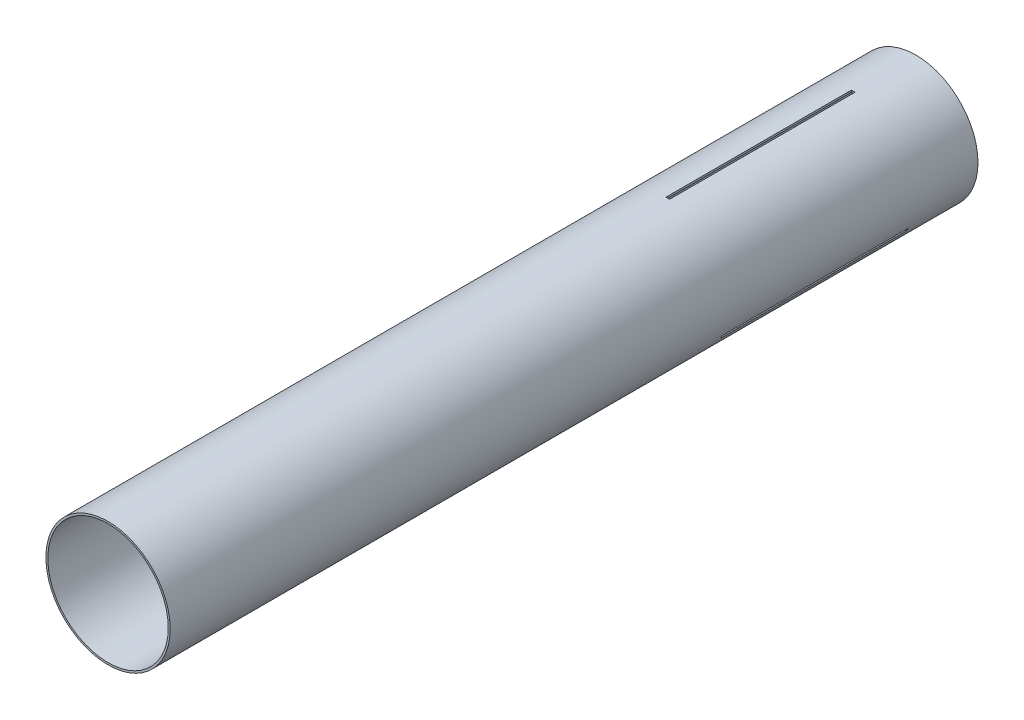
SolidWorks part; units mm, degrees
material "E-Glass Fiber"
ref_plane "Front Plane" through (0, 0, 0) normal (0, 0, 1) x (1, 0, 0)
ref_plane "Top Plane" through (0, 0, 0) normal (0, 1, 0) x (1, 0, 0)
ref_plane "Right Plane" through (0, 0, 0) normal (1, 0, 0) x (0, 0, -1)
sketch "Sketch1" plane through (0, 0, 0) normal (0, 0, 1) x (1, 0, 0)
  circle A0 centre (0, 0) radius 50.8
  circle A1 centre (0, 0) radius 49.2125
  dimension "D1" = 101.6
  dimension "D2" = 1.5875
extrude "Boss-Extrude1" add sketch "Sketch1" along normal blind 660.4
sketch "Sketch4" plane through (0, 0, 0) normal (0, 0, 1) x (1, 0, 0)
  line L0 (54.2433, -33.0478) -> (32.2463, -20.3478)
  line L1 (1.4986, 63.5) -> (-1.4986, 63.5)
  line L2 (1.4986, 63.5) -> (1.4986, 38.1)
  line L3 (1.4986, 38.1) -> (-1.4986, 38.1)
  line L4 (-1.4986, 63.5) -> (-1.4986, 38.1)
  line L5 (1.4986, 63.5) -> (-1.4986, 38.1) construction
  line L6 (1.4986, 38.1) -> (-1.4986, 63.5) construction
  line L7 (54.2433, -33.0478) -> (55.7419, -30.4522)
  line L8 (55.7419, -30.4522) -> (33.7449, -17.7522)
  line L9 (32.2463, -20.3478) -> (33.7449, -17.7522)
  line L10 (-55.7419, -30.4522) -> (-33.7449, -17.7522)
  line L11 (-55.7419, -30.4522) -> (-54.2433, -33.0478)
  line L12 (-54.2433, -33.0478) -> (-32.2463, -20.3478)
  line L13 (-33.7449, -17.7522) -> (-32.2463, -20.3478)
  line L14 (0, 0) -> (1.4986, 38.1) construction
  line L15 (0, 0) -> (32.2463, -20.3478) construction
  point P0 (0, 50.8)
  dimension "D1" = 25.4
  dimension "D2" = 2.9972
  dimension "D3" = 50.8
  dimension "D5" = 120
  dimension "D4" = 3
ref_plane "Plane1" through (0, 0, 51.1937) normal (0, 0, -1) x (-1, 0, 0)
extrude "Cut-Extrude3" cut sketch "Sketch4" along normal blind 151.6126 from offset 51.1937
sketch "Sketch5" plane through (0, 0, 0) normal (0, 1, 0) x (1, 0, 0)
  line L0 (0, 0) -> (0, -660.4) construction
  line L1 (-50.8, -660.4) -> (50.8, -660.4) construction
